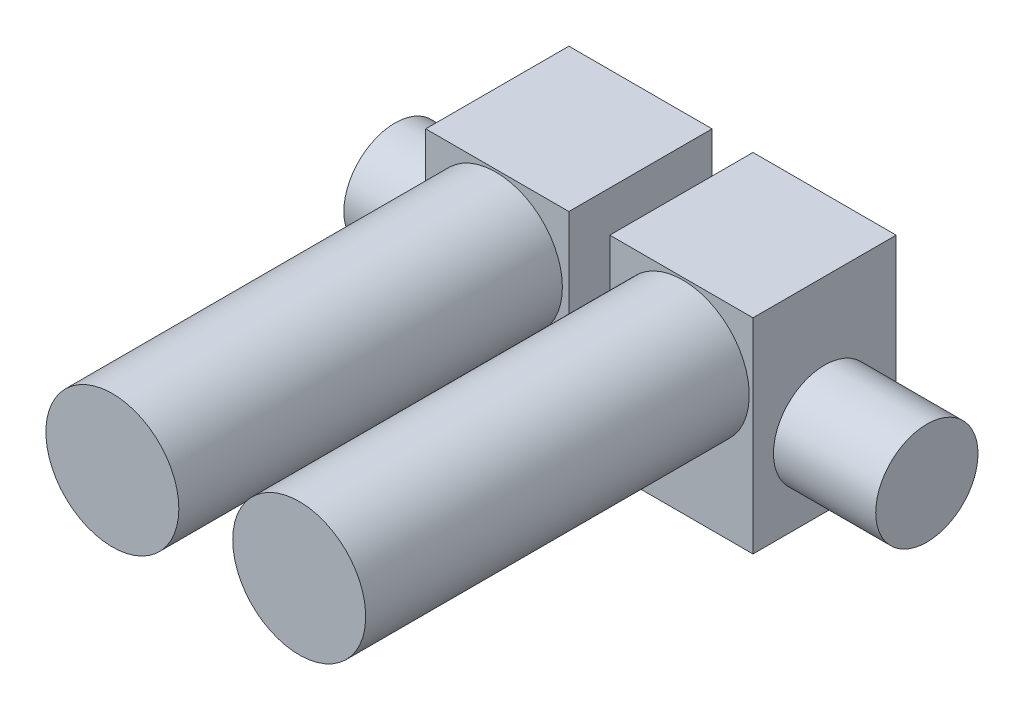
SolidWorks part; units mm, degrees
ref_plane "Plan de face" through (0, 0, 0) normal (0, 0, 1) x (1, 0, 0)
ref_plane "Plan de dessus" through (0, 0, 0) normal (0, 1, 0) x (1, 0, 0)
ref_plane "Plan de droite" through (0, 0, 0) normal (1, 0, 0) x (0, 0, -1)
sketch "Esquisse1" plane through (0, 0, 0) normal (0, 0, 1) x (1, 0, 0)
  line L1 (0, 0) -> (64, 0)
  line L2 (0, 0) -> (0, -40)
  line L3 (0, -40) -> (64, -40)
  line L4 (64, 0) -> (64, -40)
  dimension "D1" = 64
  dimension "D2" = 40
extrude "Boss.-Extru.1" add sketch "Esquisse1" along normal blind 28
sketch "Esquisse2" plane through (0, 0, 28) normal (0, 0, 1) x (1, 0, 0)
  line L0 (0, 0) -> (13.7306, 0) construction
  line L1 (64, 0) -> (0, 0) construction
  line L2 (32, 0) -> (32, -40) construction
  line L3 (0, -40) -> (64, -40) construction
  line L4 (0, 0) -> (0, -13.4552) construction
  line L5 (0, 0) -> (0, -40) construction
  line L6 (13.7306, 0) -> (13.7306, -40) construction
  line L7 (0, -13.4552) -> (64, -13.4552) construction
  line L8 (64, -40) -> (64, 0) construction
  circle A0 centre (13.7306, -13.4552) radius 13
  circle A1 centre (50.2694, -13.4552) radius 13
extrude "Boss.-Extru.2" add sketch "Esquisse2" along normal blind 75
sketch "Esquisse3" plane through (0, 0, 0) normal (-1, 0, 0) x (0, 0, 1)
  line L0 (0, -40) -> (0, -26) construction
  line L1 (0, 0) -> (0, -40) construction
  line L2 (0, -40) -> (14, -40) construction
  line L3 (28, -40) -> (0, -40) construction
  line L4 (14, -40) -> (14, 0) construction
  line L5 (28, 0) -> (0, 0) construction
  line L6 (0, -26) -> (28, -26) construction
  line L7 (28, 0) -> (28, -40) construction
  circle A0 centre (14, -26) radius 10
  dimension "D1" = 20
  dimension "D2" = 14
  dimension "D3" = 14
extrude "Boss.-Extru.3" add sketch "Esquisse3" along normal blind 20
sketch "Esquisse4" plane through (64, 0, 0) normal (1, 0, 0) x (0, 0, -1)
  line L0 (0, -40) -> (-14, -40) construction
  line L1 (-28, -40) -> (0, -40) construction
  line L2 (0, -40) -> (0, -25) construction
  line L3 (0, -40) -> (0, 0) construction
  line L4 (-14, -40) -> (-14, 0) construction
  line L5 (-28, 0) -> (0, 0) construction
  line L6 (0, -25) -> (-28, -25) construction
  line L7 (-28, -40) -> (-28, 0) construction
  circle A0 centre (-14, -25) radius 10
  dimension "D1" = 15
  dimension "D2" = 14
  dimension "D3" = 20
extrude "Boss.-Extru.4" add sketch "Esquisse4" along normal blind 20
sketch "Esquisse9" plane through (0, 0, 28) normal (0, 0, 1) x (1, 0, 0)
  line L0 (0, -40) -> (64, -40) construction
  line L2 (36, -40) -> (28, -40)
  line L4 (36, -40) -> (36, 0)
  line L5 (36, 0) -> (28, 0)
  line L6 (28, -40) -> (28, 0)
  line L7 (64, 0) -> (0, 0) construction
  line L8 (64, -40) -> (64, 0) construction
  line L9 (0, 0) -> (0, -40) construction
  dimension "D1" = 28
  dimension "D2" = 28
extrude "Enlèv. mat.-Extru.1" cut sketch "Esquisse9" against normal blind 28
